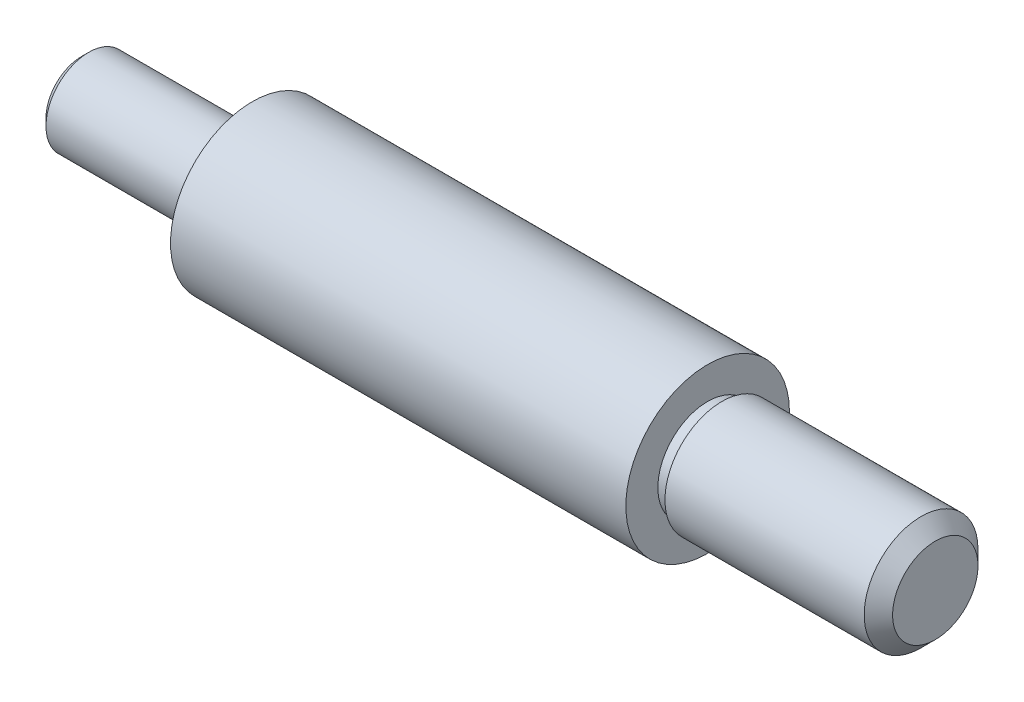
SolidWorks part; units mm, degrees
ref_plane "Front Plane" through (0, 0, 0) normal (0, 0, 1) x (1, 0, 0)
ref_plane "Top Plane" through (0, 0, 0) normal (0, 1, 0) x (1, 0, 0)
ref_plane "Right Plane" through (0, 0, 0) normal (1, 0, 0) x (0, 0, -1)
sketch "Sketch1" plane through (0, 0, 0) normal (0, 0, 1) x (1, 0, 0)
  line L1 (0, 0) -> (30, 0)
  line L2 (0, 7) -> (0, 8)
  line L3 (0, 8) -> (30, 8)
  line L4 (30, 0) -> (30, 8)
  line L5 (0, 0) -> (-2, 0)
  line L7 (0, 7) -> (-2, 7)
  line L9 (-2, 0) -> (-66, 0)
  line L10 (-2, 7) -> (-2, 11.5)
  line L11 (-2, 11.5) -> (-66, 11.5)
  line L12 (-66, 5) -> (-66, 11.5)
  line L13 (-66, 0) -> (-68, 0)
  line L15 (-66, 5) -> (-68, 5)
  line L17 (-68, 0) -> (-90, 0)
  line L18 (-68, 5) -> (-68, 6)
  line L19 (-68, 6) -> (-90, 6)
  line L20 (-90, 0) -> (-90, 6)
revolve "Revolve1" add sketch "Sketch1" angle 360 about L17
chamfer "Chamfer1" distance 2 1 edges at (30, 0, -8)
chamfer "Chamfer2" distance 1 angle 45 1 edges at (-90, 0, -6)
